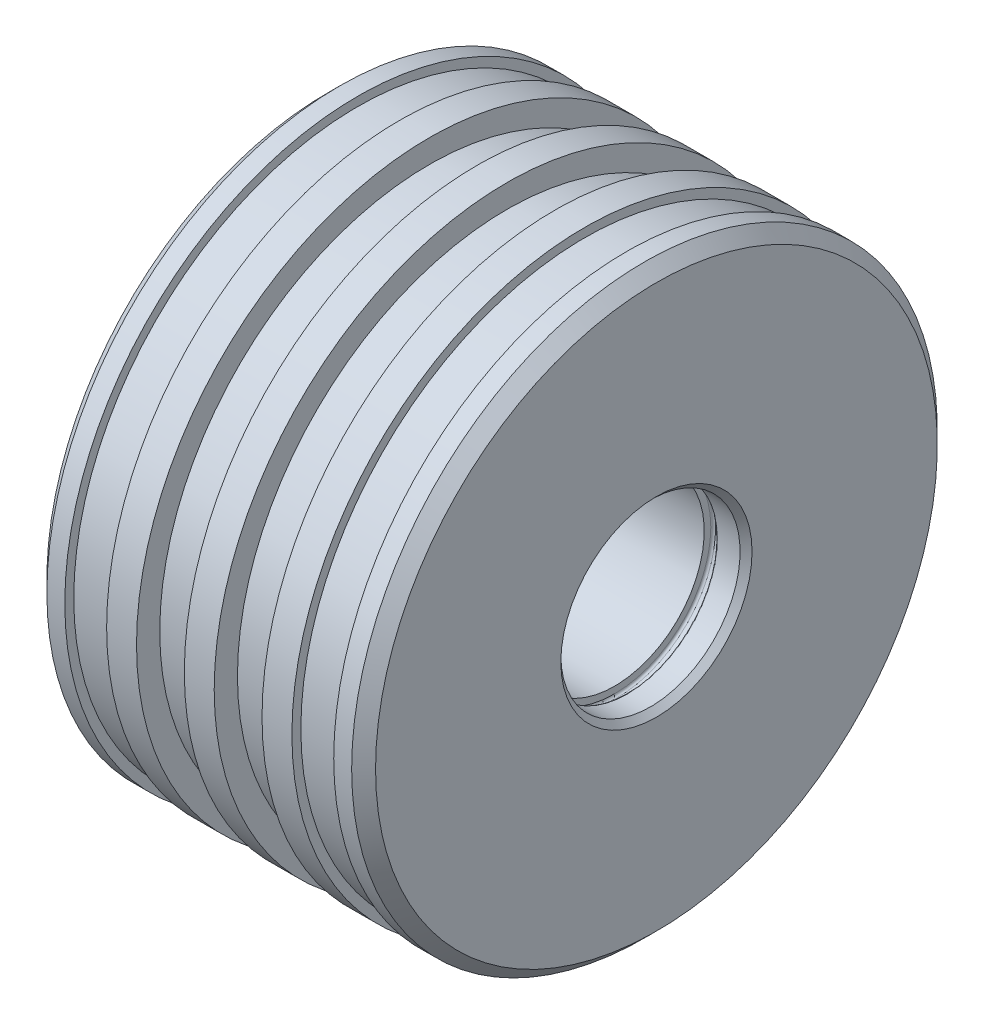
SolidWorks part; units mm, degrees
ref_plane "Front Plane" through (0, 0, 0) normal (0, 0, 1) x (1, 0, 0)
ref_plane "Top Plane" through (0, 0, 0) normal (0, 1, 0) x (1, 0, 0)
ref_plane "Right Plane" through (0, 0, 0) normal (1, 0, 0) x (0, 0, -1)
sketch "Sketch3" plane through (0, 0, 0) normal (0, 0, 1) x (1, 0, 0)
  line L0 (-27.5, 0) -> (-22.5, 0)
  line L1 (-10.5, 30.11) -> (-2.5, 30.11)
  line L2 (27.5, 30.11) -> (27.5, 0)
  line L3 (-27.5, 30.11) -> (-27.5, 0)
  line L4 (-27.5, -15) -> (27.5, -15) construction
  line L5 (-22.5, 0) -> (-22.5, 1.5)
  line L6 (-22.5, 1.5) -> (-20.5, 1.5)
  line L7 (-20.5, 1.5) -> (-20.5, 0)
  line L8 (-2.5, 30.11) -> (-2.5, 34)
  line L9 (20.5, 1.5) -> (20.5, 0)
  line L10 (22.5, 0) -> (22.5, 1.5)
  line L11 (22.5, 1.5) -> (20.5, 1.5)
  line L12 (-20.5, 0) -> (-1, 0)
  line L13 (22.5, 0) -> (27.5, 0)
  line L14 (-1, 1.5) -> (-1, 0)
  line L15 (-1, 1.5) -> (1, 1.5)
  line L16 (1, 1.5) -> (1, 0)
  line L17 (1, 0) -> (20.5, 0)
  line L18 (-27.5, 30.11) -> (-27.5, 34)
  line L19 (-27.5, 34) -> (-22.5, 34)
  line L20 (-22.5, 34) -> (-22.5, 32.5)
  line L21 (-22.5, 32.5) -> (-15.5, 32.5)
  line L22 (-15.5, 32.5) -> (-15.5, 34)
  line L23 (-15.5, 34) -> (-10.5, 34)
  line L24 (-10.5, 34) -> (-10.5, 30.11)
  line L25 (-2.5, 34) -> (2.5, 34)
  line L26 (2.5, 34) -> (2.5, 30.11)
  line L27 (27.5, 30.11) -> (27.5, 34)
  line L28 (0, 30.11) -> (0, -23.1208) construction
  line L29 (27.5, 34) -> (22.5, 34)
  line L30 (22.5, 34) -> (22.5, 32.5)
  line L31 (22.5, 32.5) -> (15.5, 32.5)
  line L32 (15.5, 32.5) -> (15.5, 34)
  line L33 (15.5, 34) -> (10.5, 34)
  line L34 (10.5, 34) -> (10.5, 30.11)
  line L35 (2.5, 30.11) -> (10.5, 30.11)
  point P4 (0, 0)
  dimension "D1" = 55
  dimension "D2" = 45.11
  dimension "D3" = 15
  dimension "D4" = 2
  dimension "D5" = 5
  dimension "D6" = 16.5
  dimension "D7" = 26.5
  dimension "D8" = 2
  dimension "D9" = 5
  dimension "D10" = 5
  dimension "D11" = 7
  dimension "D12" = 49
  dimension "D13" = 47.5
  dimension "D14" = 8
  dimension "D15" = 5
  dimension "D16" = 8
  dimension "D17" = 5
  dimension "D18" = 7
revolve "Revolve1" add sketch "Sketch3" angle 360 about L4
chamfer "Chamfer2" distance 2 angle 45 2 edges at (27.5, -15, 49) (-27.5, -15, 49)
chamfer "Chamfer3" distance 1 angle 45 2 edges at (-27.5, -15, 15) (27.5, -15, 15)
fillet "Fillet1" radius 0.4 3 edges at (20.5, -15, 16.5) (-1, -15, 16.5) (-22.5, -15, 16.5)
fillet "Fillet2" radius 0.2 3 edges at (22.5, -15, 15) (1, -15, 15) (-20.5, -15, 15)
ref_plane "Plane1" through (0, 0, 0) normal (1, 0, 0) x (0, 0, -1)
ref_plane "Plane2" through (-21.5, 0, 0) normal (1, 0, 0) x (0, 0, -1)
